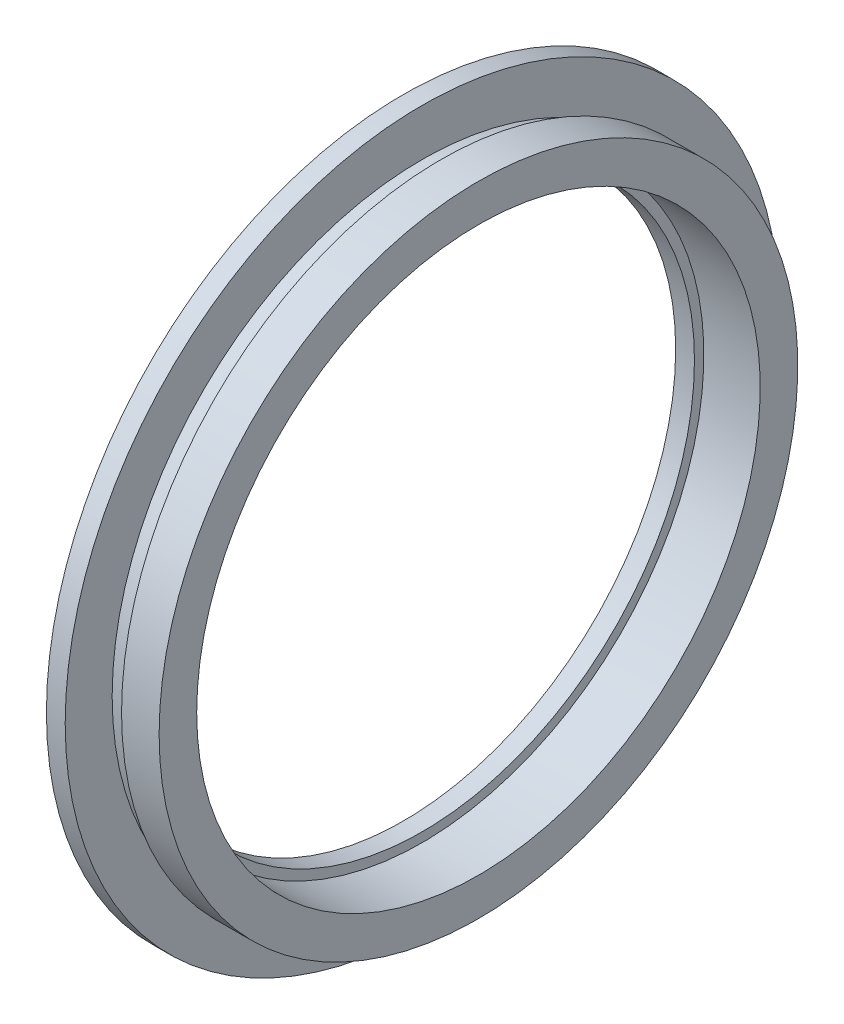
SolidWorks part; units mm, degrees
ref_plane "Front Plane" through (0, 0, 0) normal (0, 0, 1) x (1, 0, 0)
ref_plane "Top Plane" through (0, 0, 0) normal (0, 1, 0) x (1, 0, 0)
ref_plane "Right Plane" through (0, 0, 0) normal (1, 0, 0) x (0, 0, -1)
sketch "Sketch1" plane through (0, 0, 0) normal (0, 0, 1) x (1, 0, 0)
  line L0 (0, 19) -> (0, 0) construction
  line L1 (0, 0) -> (4, 0) construction
  line L2 (0, 19) -> (1, 19)
  line L3 (1, 19) -> (1, 16.5)
  line L4 (1, 16.5) -> (2, 16.5)
  line L5 (2, 16.5) -> (2, 17)
  line L6 (2, 17) -> (4, 17)
  line L7 (4, 17) -> (4, 15)
  line L8 (1, 14.5) -> (0, 14.5)
  line L9 (0, 14.5) -> (0, 19)
  line L10 (1, 14.5) -> (1, 15)
  line L11 (1, 15) -> (4, 15)
  dimension "D1" = 38
  dimension "D2" = 29
  dimension "D3" = 1
  dimension "D4" = 4
  dimension "D5" = 0.5
  dimension "D6" = 34
  dimension "D7" = 1
  dimension "D8" = 30
revolve "Revolve1" add sketch "Sketch1" angle 360 about L1
